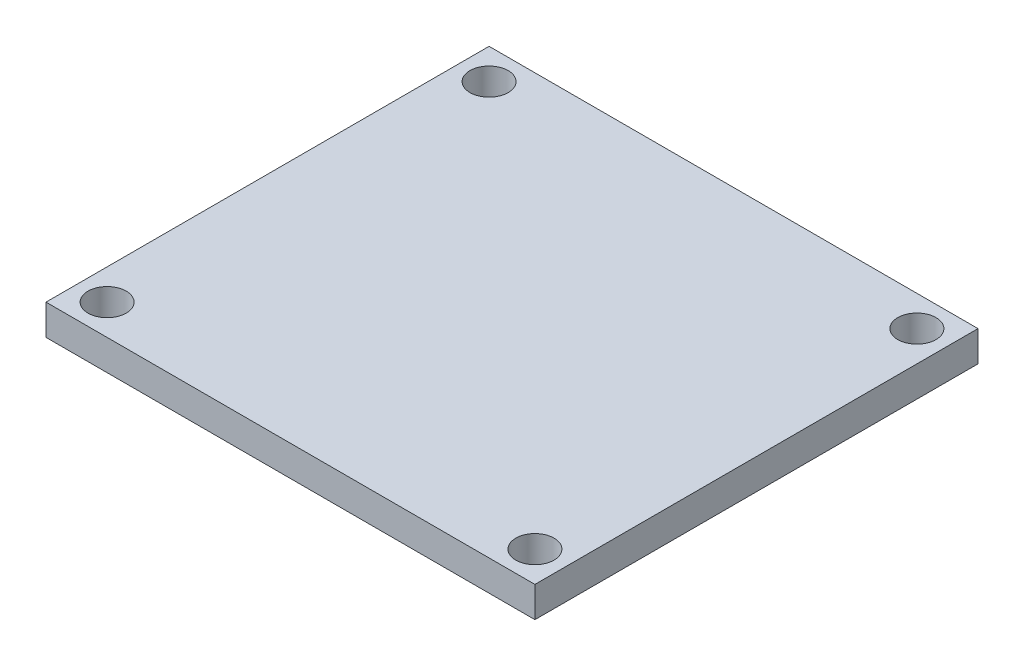
SolidWorks part; units mm, degrees
ref_plane "Front Plane" through (0, 0, 0) normal (0, 0, 1) x (1, 0, 0)
ref_plane "Top Plane" through (0, 0, 0) normal (0, 1, 0) x (1, 0, 0)
ref_plane "Right Plane" through (0, 0, 0) normal (1, 0, 0) x (0, 0, -1)
sketch "Sketch1" plane through (0, 0, 0) normal (0, 1, 0) x (1, 0, 0)
  line L1 (0, 0) -> (40.64, 0)
  line L2 (0, 0) -> (0, -36.83)
  line L3 (0, -36.83) -> (40.64, -36.83)
  line L4 (40.64, 0) -> (40.64, -36.83)
  line L5 (2.54, -34.29) -> (38.1, -34.29) construction
  line L6 (2.54, -34.29) -> (2.54, -2.54) construction
  line L7 (2.54, -2.54) -> (38.1, -2.54) construction
  line L8 (38.1, -34.29) -> (38.1, -2.54) construction
  circle A0 centre (2.54, -2.54) radius 1.5875
  circle A1 centre (2.54, -34.29) radius 1.5875
  circle A2 centre (38.1, -2.54) radius 1.5875
  circle A3 centre (38.1, -34.29) radius 1.5875
  point P13 (38.1, -33.8141)
  dimension "D3" = 3.175
  dimension "D4" = 3.175
  dimension "D5" = 3.175
  dimension "D6" = 3.175
  dimension "D1" = 36.83
  dimension "D2" = 40.64
  dimension "D7" = 2.54
  dimension "D8" = 2.54
  dimension "D10" = 2.54
  dimension "D11" = 2.54
extrude "Boss-Extrude1" add sketch "Sketch1" along normal blind 2.54
